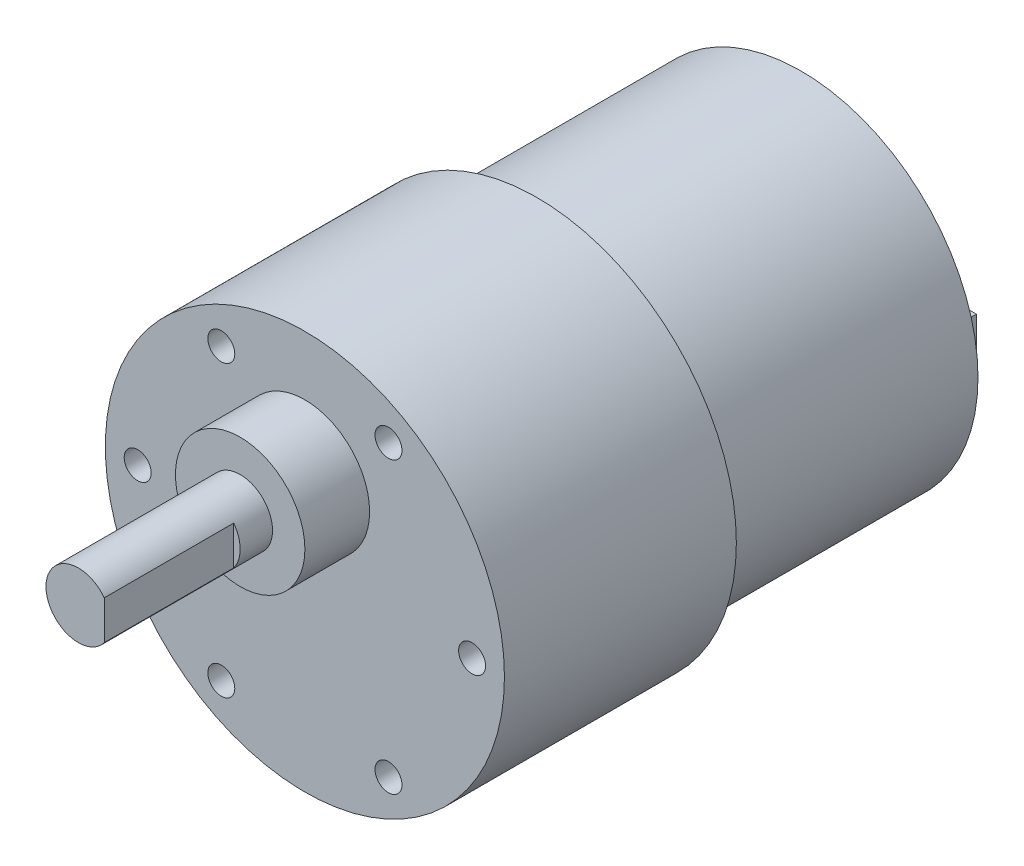
SolidWorks part; units mm, degrees
ref_plane "前视基准面" through (0, 0, 0) normal (0, 0, 1) x (1, 0, 0)
ref_plane "上视基准面" through (0, 0, 0) normal (0, 1, 0) x (1, 0, 0)
ref_plane "右视基准面" through (0, 0, 0) normal (1, 0, 0) x (0, 0, -1)
sketch "草图1" plane through (0, 0, 0) normal (0, 0, 1) x (1, 0, 0)
  circle A0 centre (0, 0) radius 18.5
  dimension "D1" = 37
extrude "减速箱_直径37_长21.5" add sketch "草图1" along normal blind 21.5 from offset 21.5
sketch "草图2" plane through (0, 0, 0) normal (0, 0, 1) x (1, 0, 0)
  circle A0 centre (0, 0) radius 16.4
  dimension "D1" = 32.8
extrude "电机壳_直径32.8_长23" add sketch "草图2" along normal blind 23 from offset 44.5
sketch "草图3" plane through (0, 0, 0) normal (0, 0, 1) x (1, 0, 0)
  circle A0 centre (0, 0) radius 16.4
  dimension "D1" = 32.8
extrude "编码器PCB" add sketch "草图3" along normal blind 1.5 from offset 46
sketch "草图4" plane through (0, 0, 0) normal (0, 0, 1) x (1, 0, 0)
  circle A0 centre (0, 0) radius 6.75
  dimension "D1" = 13.5
extrude "编码器磁环" add sketch "草图4" along normal blind 4 from offset 50
sketch "草图5" plane through (0, 0, 0) normal (0, 0, 1) x (1, 0, 0)
  line L1 (-6.75, -11.5) -> (6.75, -11.5)
  line L2 (-6.75, -11.5) -> (-6.75, -4.5)
  line L3 (-6.75, -4.5) -> (6.75, -4.5)
  line L4 (6.75, -11.5) -> (6.75, -4.5)
  line L5 (-6.75, -11.5) -> (6.75, -4.5) construction
  line L6 (-6.75, -4.5) -> (6.75, -11.5) construction
  point P0 (0, -8)
  dimension "D1" = 6.75
  dimension "D2" = 4.5
  dimension "D3" = 8
extrude "XH2.54连接器_外形简化" add sketch "草图5" along normal blind 9.5 from offset 55.5
sketch "草图6" plane through (0, 0, 0) normal (0, 0, 1) x (1, 0, 0)
  circle A0 centre (0, 7) radius 6
  dimension "D1" = 12
  dimension "D2" = 7
extrude "偏心7mm_轴台直径12" add sketch "草图6" along normal blind 6
sketch "草图7" plane through (0, 0, 0) normal (0, 0, 1) x (1, 0, 0)
  circle A0 centre (0, 7) radius 3
  dimension "D1" = 6
  dimension "D2" = 7
extrude "输出轴直径6" add sketch "草图7" along normal blind 3 from offset 6
sketch "草图8" plane through (0, 0, 0) normal (0, 0, 1) x (1, 0, 0)
  line L0 (2.4, 5.2) -> (2.4, 8.8)
  arc A0 (2.4, 8.8) -> (2.4, 5.2) centre (0, 7) ccw
extrude "D轴_5.4对边_削平长12" add sketch "草图8" along normal blind 12 from offset 9
sketch "草图9" plane through (0, 0, 0) normal (0, 0, 1) x (1, 0, 0)
  circle A0 centre (15.5, 0) radius 1.25
  circle A1 centre (7.75, 13.4234) radius 1.25
  circle A2 centre (-7.75, 13.4234) radius 1.25
  circle A3 centre (-15.5, 0) radius 1.25
  circle A4 centre (-7.75, -13.4234) radius 1.25
  circle A5 centre (7.75, -13.4234) radius 1.25
extrude "6xM3安装底孔_深3_牙型简化" cut sketch "草图9" against normal blind 3
